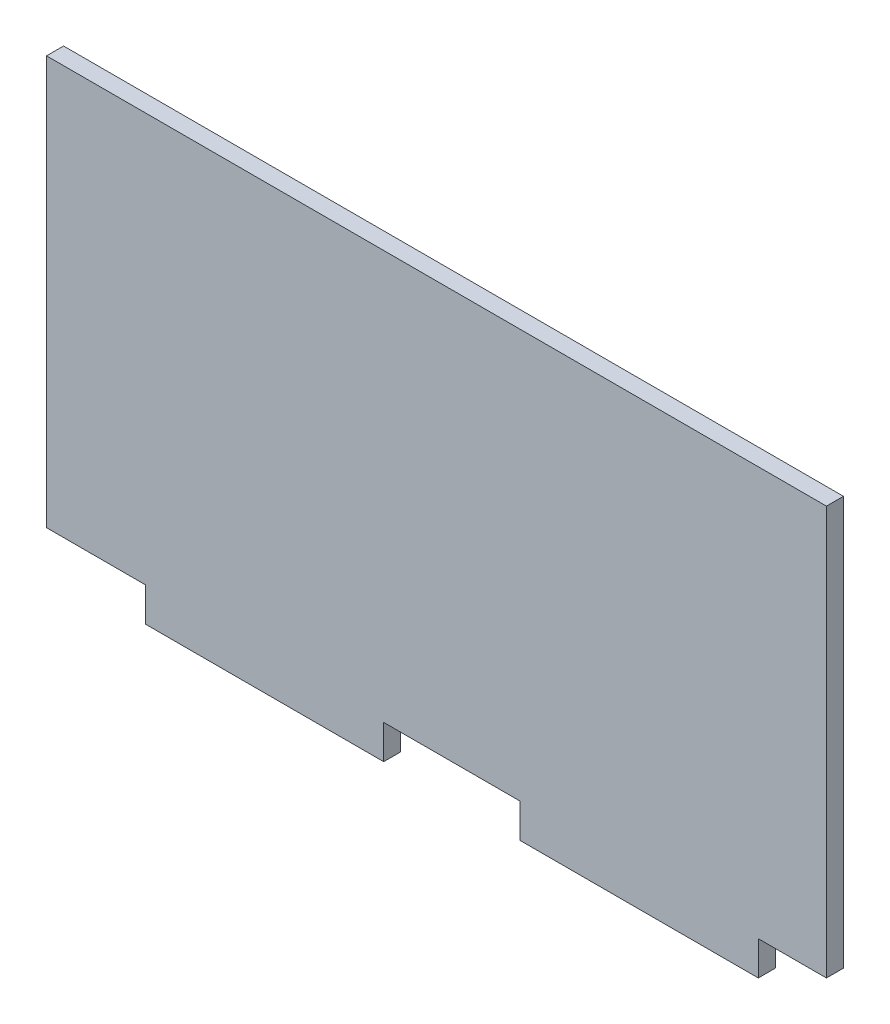
SolidWorks part; units mm, degrees
material "Balsa"
ref_plane "Plan de face" through (0, 0, 0) normal (0, 0, 1) x (1, 0, 0)
ref_plane "Plan de dessus" through (0, 0, 0) normal (0, 1, 0) x (1, 0, 0)
ref_plane "Plan de droite" through (0, 0, 0) normal (1, 0, 0) x (0, 0, -1)
sketch "Esquisse1" plane through (0, 0, 0) normal (0, 0, 1) x (1, 0, 0)
  line L0 (-84.624, 0) -> (-55.624, 0)
  line L1 (-55.624, 0) -> (-55.624, -10)
  line L2 (-55.624, -10) -> (14.376, -10)
  line L3 (14.376, -10) -> (14.376, 0)
  line L4 (14.376, 0) -> (54.376, 0)
  line L5 (54.376, 0) -> (54.376, -10)
  line L6 (54.376, -10) -> (124.376, -10)
  line L7 (124.376, -10) -> (124.376, 0)
  line L8 (124.376, 0) -> (144.376, 0)
  line L9 (144.376, 0) -> (144.376, 120)
  line L10 (144.376, 120) -> (-84.624, 120)
  line L11 (-84.624, 120) -> (-84.624, 0)
  dimension "D1" = 229
  dimension "D2" = 29
  dimension "D3" = 70
  dimension "D4" = 40
  dimension "D5" = 70
  dimension "D6" = 20
  dimension "D7" = 120
  dimension "D8" = 10
  dimension "D9" = 10
  dimension "D10" = 120
extrude "Boss.-Extru.1" add sketch "Esquisse1" along normal blind 5 contours L11 L0 L1 L2 L3 L4 L5 L6 L7 L8 L9 L10
